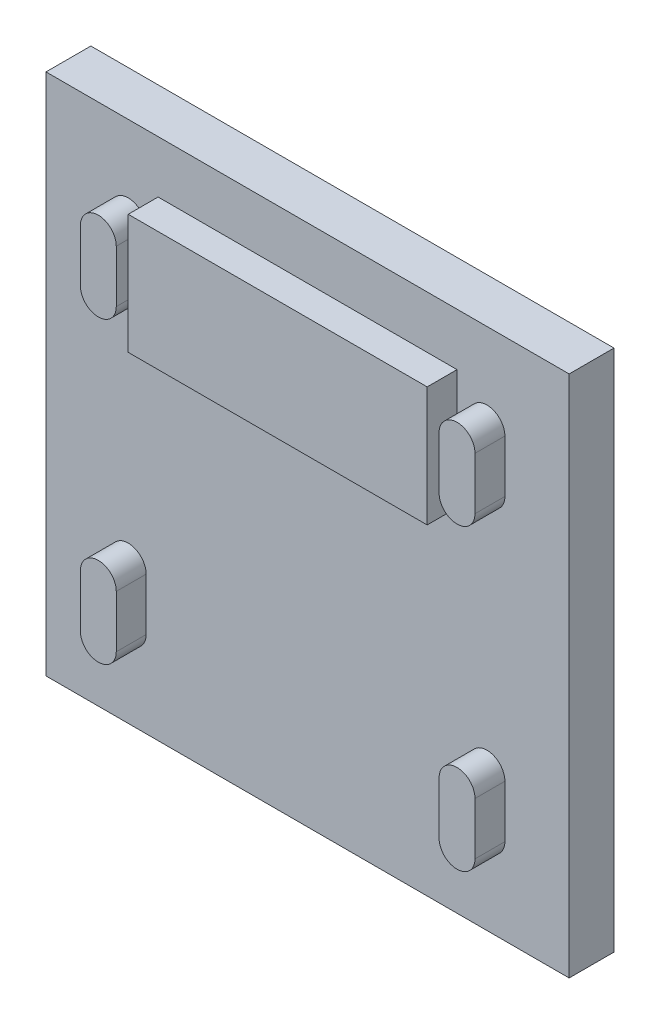
SolidWorks part; units mm, degrees
ref_plane "Front Plane" through (0, 0, 0) normal (0, 0, 1) x (1, 0, 0)
ref_plane "Top Plane" through (0, 0, 0) normal (0, 1, 0) x (1, 0, 0)
ref_plane "Right Plane" through (0, 0, 0) normal (1, 0, 0) x (0, 0, -1)
sketch "Sketch2" plane through (0, 0, 0) normal (0, 0, 1) x (1, 0, 0)
  line L1 (17.5, -17.5) -> (-17.5, -17.5)
  line L2 (17.5, -17.5) -> (17.5, 17.5)
  line L3 (17.5, 17.5) -> (-17.5, 17.5)
  line L4 (-17.5, -17.5) -> (-17.5, 17.5)
  line L5 (17.5, -17.5) -> (-17.5, 17.5) construction
  line L6 (17.5, 17.5) -> (-17.5, -17.5) construction
  point P0 (0, 0)
  dimension "D1" = 35
  dimension "D2" = 35
extrude "Boss-Extrude1" add sketch "Sketch2" along normal blind 3
sketch "Sketch3" plane through (0, 0, 3) normal (0, 0, 1) x (1, 0, 0)
  line L0 (-12, 8.25) -> (-12, 11.75) construction
  line L1 (-13.2, 8.25) -> (-13.2, 11.75)
  line L2 (-10.8, 8.25) -> (-10.8, 11.75)
  line L3 (-12, -11.75) -> (-12, -8.25) construction
  line L4 (-13.2, -11.75) -> (-13.2, -8.25)
  line L5 (-10.8, -11.75) -> (-10.8, -8.25)
  line L6 (12, -11.75) -> (12, -8.25) construction
  line L7 (10.8, -11.75) -> (10.8, -8.25)
  line L8 (13.2, -11.75) -> (13.2, -8.25)
  line L9 (12, 8.25) -> (12, 11.75) construction
  line L10 (10.8, 8.25) -> (10.8, 11.75)
  line L11 (13.2, 8.25) -> (13.2, 11.75)
  line L13 (-10, 6) -> (10, 6)
  line L14 (-10, 6) -> (-10, 14)
  line L15 (-10, 14) -> (10, 14)
  line L16 (10, 6) -> (10, 14)
  line L17 (-10, 6) -> (10, 14) construction
  line L18 (-10, 14) -> (10, 6) construction
  arc A0 (-13.2, 8.25) -> (-10.8, 8.25) centre (-12, 8.25) ccw
  arc A1 (-10.8, 11.75) -> (-13.2, 11.75) centre (-12, 11.75) ccw
  arc A2 (-13.2, -11.75) -> (-10.8, -11.75) centre (-12, -11.75) ccw
  arc A3 (-10.8, -8.25) -> (-13.2, -8.25) centre (-12, -8.25) ccw
  arc A4 (10.8, -11.75) -> (13.2, -11.75) centre (12, -11.75) ccw
  arc A5 (13.2, -8.25) -> (10.8, -8.25) centre (12, -8.25) ccw
  arc A6 (10.8, 8.25) -> (13.2, 8.25) centre (12, 8.25) ccw
  arc A7 (13.2, 11.75) -> (10.8, 11.75) centre (12, 11.75) ccw
  point P2 (-12, 10)
  point P7 (-12, -10)
  point P14 (12, -10)
  point P21 (12, 10)
  point P32 (0, 10)
  dimension "D2" = 1.2
  dimension "D4" = 10
  dimension "D1" = 3.5
  dimension "D3" = 12
  dimension "D5" = 10
  dimension "D6" = 10
  dimension "D7" = 10
  dimension "D8" = 12
  dimension "D9" = 20
  dimension "D10" = 8
  dimension "D11" = 10
extrude "Boss-Extrude2" add sketch "Sketch3" along normal blind 2
